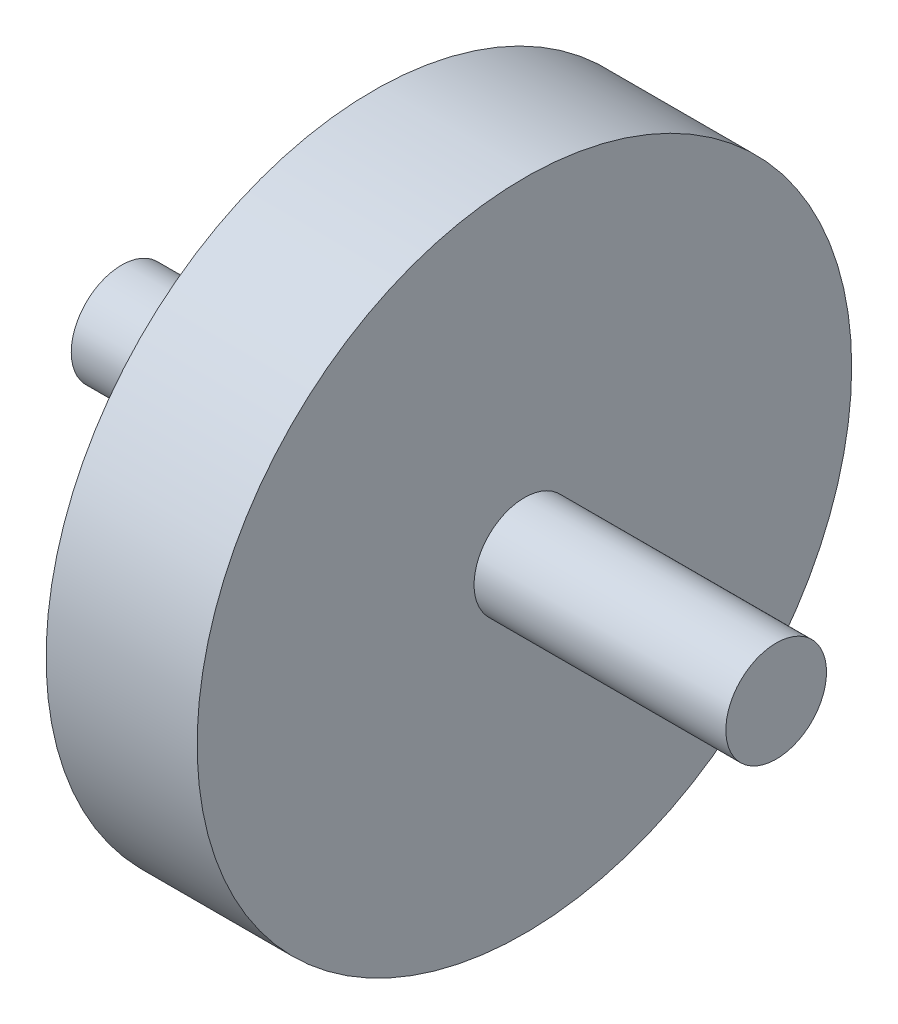
SolidWorks part; units mm, degrees
ref_plane "Front Plane" through (0, 0, 0) normal (0, 0, 1) x (1, 0, 0)
ref_plane "Top Plane" through (0, 0, 0) normal (0, 1, 0) x (1, 0, 0)
ref_plane "Right Plane" through (0, 0, 0) normal (1, 0, 0) x (0, 0, -1)
sketch "Sketch1" plane through (0, 0, 0) normal (1, 0, 0) x (0, 0, -1)
  circle A0 centre (0, 0) radius 65
  dimension "D1" = 130
extrude "Boss-Extrude1" add sketch "Sketch1" along normal blind 30
sketch "Sketch2" plane through (30, 0, 0) normal (1, 0, 0) x (0, 0, -1)
  circle A0 centre (0, 0) radius 10
  dimension "D1" = 20
extrude "Boss-Extrude2" add sketch "Sketch2" along normal blind 50
sketch "Sketch3" plane through (0, 0, 0) normal (-1, 0, 0) x (0, 0, 1)
  circle A0 centre (0, 0) radius 10
  dimension "D1" = 20
extrude "Boss-Extrude3" add sketch "Sketch3" along normal blind 50
